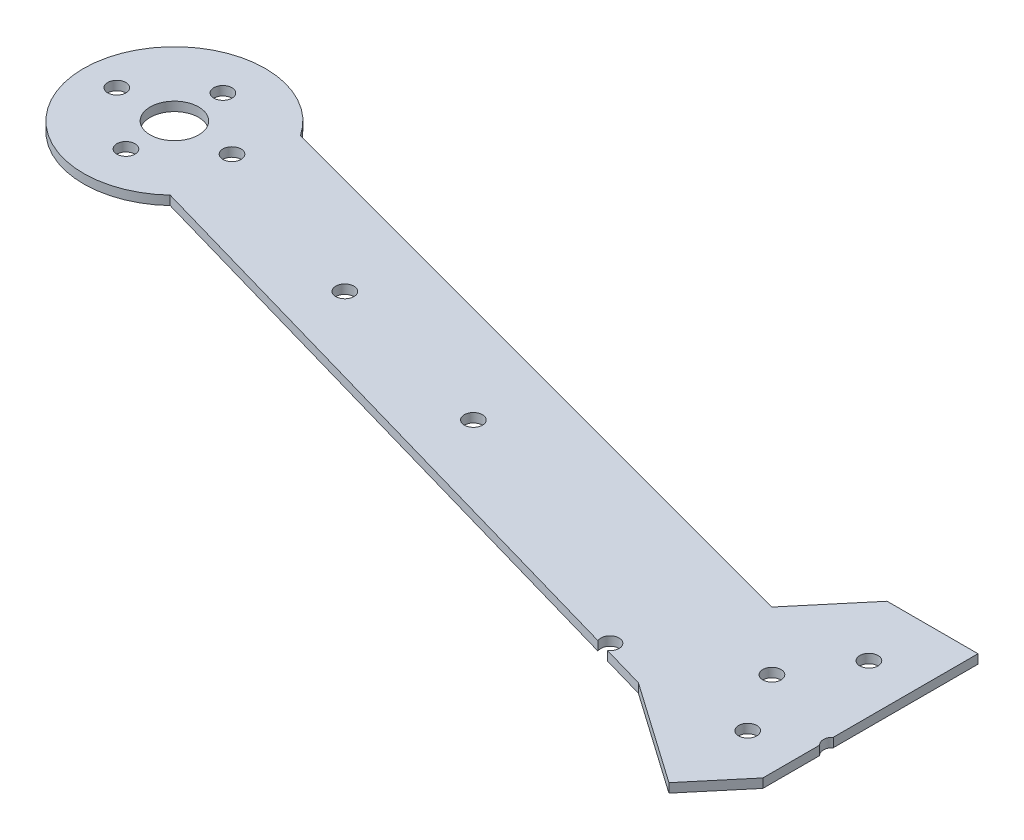
SolidWorks part; units mm, degrees
ref_plane "Front Plane" through (0, 0, 0) normal (0, 0, 1) x (1, 0, 0)
ref_plane "Top Plane" through (0, 0, 0) normal (0, 1, 0) x (1, 0, 0)
ref_plane "Right Plane" through (0, 0, 0) normal (1, 0, 0) x (0, 0, -1)
sketch "Sketch1" plane through (0, 0, 0) normal (0, 1, 0) x (1, 0, 0)
  line L7 (0, 0) -> (0, 35.5)
  line L8 (0, 35.5) -> (-15, 35.5)
  line L9 (-15, 35.5) -> (-23.6776, 25.1584)
  line L10 (-23.6776, 25.1584) -> (-129.9295, 53.6285)
  line L11 (0, 0) -> (-7.0707, -8.4265)
  line L12 (-7.0707, -8.4265) -> (-23.8633, 3.3318)
  line L17 (-23.8633, 3.3318) -> (-31.0343, 5.3877)
  line L20 (-23.8633, 3.3318) -> (-23.6776, 25.1584) construction
  line L21 (-142.4295, 45.3369) -> (-136.8295, 45.3369) construction
  line L23 (-142.4295, 45.3369) -> (-142.4295, 51.2621) construction
  line L33 (-105.4635, 35.4319) -> (-23.7764, 13.5439) construction
  line L36 (-142.4295, 45.3369) -> (-138.5658, 44.3017) construction
  line L37 (-33.2238, 6.0154) -> (-132.1793, 34.3855)
  arc A14 (-129.9295, 53.6285) -> (-132.1793, 34.3855) centre (-142.4295, 45.3369) ccw
  circle A15 centre (-8, 25.5) radius 1.5
  circle A16 centre (-14, 15.5) radius 1.5
  circle A17 centre (-8, 5.5) radius 1.5
  arc A18 (-31.0343, 5.3877) -> (-33.2238, 6.0154) centre (-31.86, 6.64) ccw
  circle A19 centre (1, 10.5) radius 1.5
  circle A20 centre (-142.4295, 45.3369) radius 4
  circle A29 centre (-104.0146, 35.0437) radius 1.5
  circle A30 centre (-75.0368, 27.2791) radius 1.5
  circle A31 centre (-142.4295, 53.3369) radius 1.5
  circle A32 centre (-142.4295, 37.3369) radius 1.5
  circle A33 centre (-151.9295, 45.3369) radius 1.5
  circle A34 centre (-132.9295, 45.3369) radius 1.5
  point P20 (-7.5, 35.5)
  point P55 (-142.4295, 45.3369)
  point P59 (-142.4295, 54.6869)
  dimension "D12" = 3
  dimension "D16" = 3
  dimension "D17" = 3
  dimension "D18" = 3
  dimension "D19" = 3
  dimension "D20" = 8
  dimension "D21" = 10
  dimension "D23" = 20
  dimension "D24" = 14
  dimension "D25" = 15
  dimension "D27" = 8
  dimension "D32" = 3
  dimension "D33" = 3
  dimension "D34" = 30
  dimension "D35" = 39.77
  dimension "D36" = 17.86
  dimension "D37" = 8.86
  dimension "D28" = 3
  dimension "D29" = 3
  dimension "D30" = 3
  dimension "D31" = 3
  dimension "D38" = 16
  dimension "D39" = 8
  dimension "D40" = 19
  dimension "D41" = 9.5
  dimension "D1" = 35.5
  dimension "D2" = 15
  dimension "D3" = 13.5
  dimension "D4" = 130
  dimension "D5" = 115
  dimension "D6" = 110
  dimension "D7" = 90
  dimension "D8" = 11
  dimension "D9" = 140
  dimension "D10" = 20.5
  dimension "D11" = 95
  dimension "D13" = 15
  dimension "D14" = 12.5
  dimension "D15" = 74.49
  dimension "D22" = 30
  dimension "D26" = 15
extrude "Boss-Extrude1" add sketch "Sketch1" along normal blind 1.5
